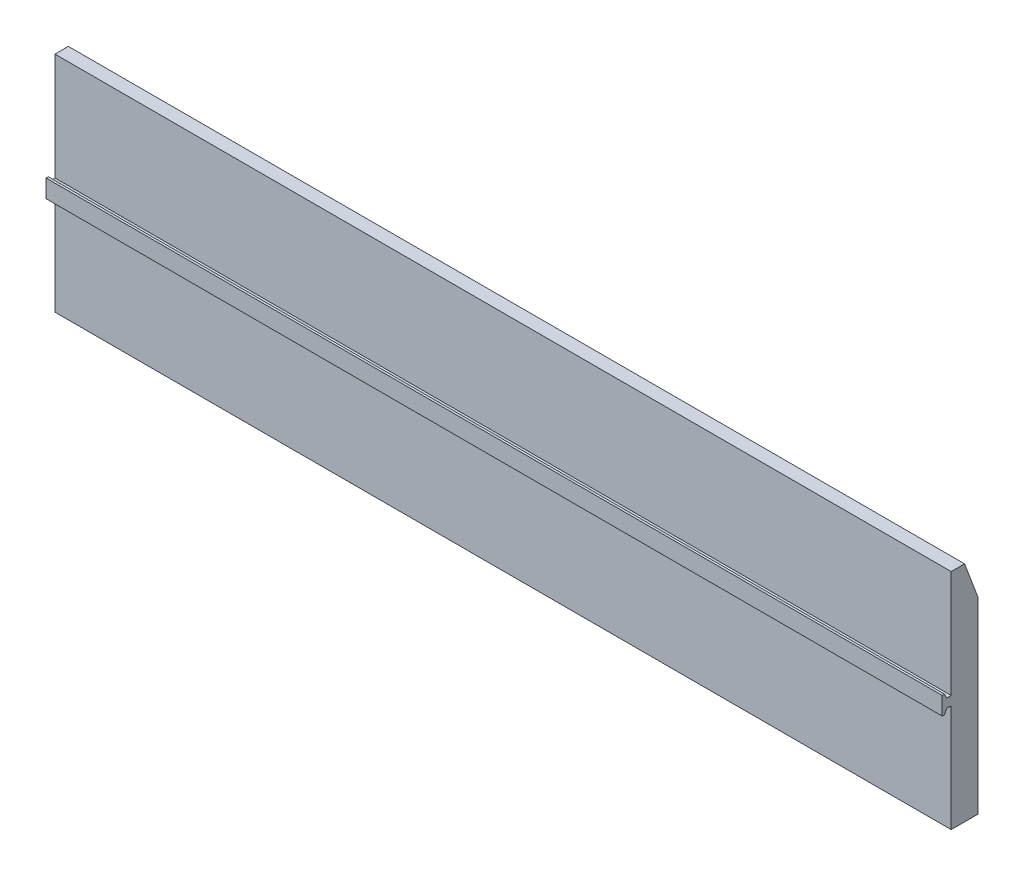
SolidWorks part; units mm, degrees
ref_plane "前视基准面" through (0, 0, 0) normal (0, 0, 1) x (1, 0, 0)
ref_plane "上视基准面" through (0, 0, 0) normal (0, 1, 0) x (1, 0, 0)
ref_plane "右视基准面" through (0, 0, 0) normal (1, 0, 0) x (0, 0, -1)
other "Configuration Table"
sketch "草图7" plane through (0, 0, 0) normal (0, 1, 0) x (1, 0, 0)
  line L0 (0, 0) -> (1027.5, 0) construction
  point P4 (1027.5, 0)
  dimension "D1" = 1027.5
ref_plane "基准面4" through (1027.5, 0, 0) normal (1, 0, 0) x (0, 0, -1)
sketch "草图1" plane through (1027.5, 0, 0) normal (1, 0, 0) x (0, 0, -1)
  line L0 (-105, 300) -> (-105, 180)
  line L1 (-105, 180) -> (-110, 180)
  line L2 (-110, 180) -> (-112.5, 185)
  line L3 (-112.5, 185) -> (-115, 185)
  line L4 (-115, 185) -> (-115, 165)
  line L5 (-115, 165) -> (-112.5, 165)
  line L6 (-112.5, 165) -> (-110, 170)
  line L7 (-110, 170) -> (-105, 170)
  line L8 (-105, 170) -> (-105, 50)
  line L9 (-105, 300) -> (-90, 300)
  line L10 (-90, 300) -> (-75, 260)
  line L11 (-75, 260) -> (-75, 80)
  line L13 (-75, 50) -> (-105, 50)
  line L15 (-75, 50) -> (110, 50)
  line L17 (-75, 80) -> (110, 80)
  line L18 (110, 50) -> (110, 80)
extrude "凸台-拉伸1" add sketch "草图1" against normal blind 1002.5
sketch "草图2" plane through (0, 80, 0) normal (0, 1, 0) x (1, 0, 0)
  line L0 (25, -115) -> (1027.5, -115) construction
  line L1 (526.25, 145.125) -> (526.25, -305.1005) construction
  line L2 (25, 110) -> (1027.5, 110) construction
  line L3 (326.25, 110) -> (726.25, 110)
  line L4 (326.25, 110) -> (326.25, -75)
  line L5 (326.25, -75) -> (726.25, -75)
  line L6 (726.25, 110) -> (726.25, -75)
  line L7 (25, -75) -> (1027.5, -75) construction
  dimension "D1" = 200
  dimension "D2" = 200
extrude "切除-拉伸1" cut sketch "草图2" against normal through all both and the other way through all
sketch "草图3" plane through (0, 80, 0) normal (0, 1, 0) x (1, 0, 0)
  line L0 (25, -75) -> (1027.5, -75) construction
  line L1 (25, 110) -> (175, 110)
  line L2 (25, 110) -> (25, -75)
  line L3 (25, -75) -> (175, -75)
  line L4 (175, 110) -> (175, -75)
  line L5 (726.25, -75) -> (1027.5, -75) construction
  line L6 (1027.5, 110) -> (877.5, 110)
  line L7 (1027.5, 110) -> (1027.5, -75)
  line L8 (1027.5, -75) -> (877.5, -75)
  line L9 (877.5, 110) -> (877.5, -75)
  dimension "D1" = 150
  dimension "D2" = 150
extrude "切除-拉伸2" cut sketch "草图3" against normal through all both and the other way through all
ref_plane "基准面1" through (801.875, 0, 0) normal (1, 0, 0) x (0, 0, -1)
ref_plane "基准面2" through (250.625, 0, 0) normal (1, 0, 0) x (0, 0, -1)
sketch "草图4" plane through (801.875, 0, 0) normal (1, 0, 0) x (0, 0, -1)
  line L0 (-15, 80) -> (-75, 180)
  line L1 (110, 80) -> (-75, 80) construction
  line L2 (-75, 50) -> (-75, 260) construction
  dimension "D1" = 60
  dimension "D2" = 100
sketch "草图6" plane through (0, 0, 0) normal (0, 1, 0) x (1, 0, 0)
  line L0 (0, 0) -> (1027.5, 0) construction
  point P4 (1027.5, 0)
  dimension "D1" = 1027.5
ref_plane "基准面3" through (1027.5, 0, 0) normal (1, 0, 0) x (0, 0, -1)
sketch "草图8" plane through (0, 80, 0) normal (0, 1, 0) x (1, 0, 0)
  line L0 (726.25, 110) -> (877.5, 110) construction
  line L1 (45.4317, 225.7795) -> (976.8872, 225.7795)
  line L2 (45.4317, 225.7795) -> (45.4317, 45)
  line L3 (45.4317, 45) -> (976.8872, 45)
  line L4 (976.8872, 225.7795) -> (976.8872, 45)
  dimension "D1" = 65
extrude "切除-拉伸3" cut sketch "草图8" against normal through all both and the other way through all
sketch "草图9" plane through (0, 80, 0) normal (0, 1, 0) x (1, 0, 0)
  circle A0 centre (215, -15) radius 12
  circle A1 centre (286.25, -15) radius 12
  circle A2 centre (766.25, -15) radius 12
  circle A3 centre (837.5, -15) radius 12
extrude "切除-拉伸4" cut sketch "草图9" against normal through all both and the other way through all
